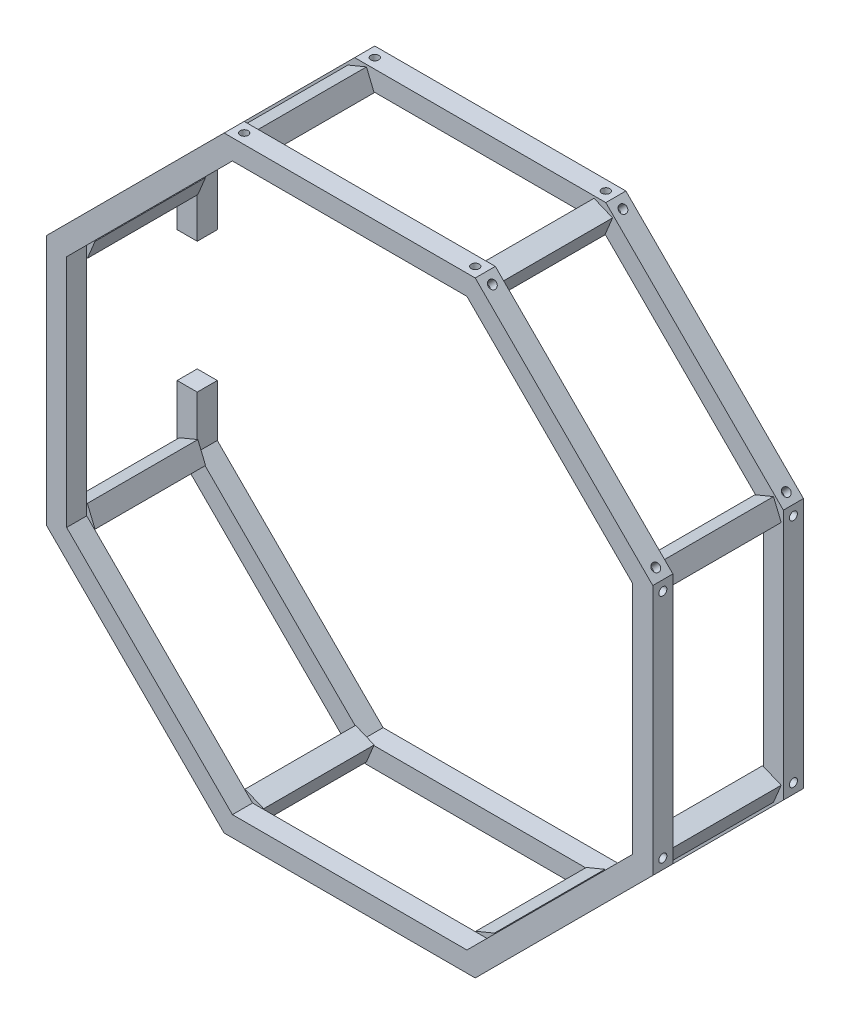
SolidWorks part; units mm, degrees
ref_plane "Front Plane" through (0, 0, 0) normal (0, 0, 1) x (1, 0, 0)
ref_plane "Top Plane" through (0, 0, 0) normal (0, 1, 0) x (1, 0, 0)
ref_plane "Right Plane" through (0, 0, 0) normal (1, 0, 0) x (0, 0, -1)
sketch "Sketch1" plane through (0, 0, 0) normal (0, 0, 1) x (1, 0, 0)
  line L7 (301.7767, 125) -> (125, 301.7767)
  line L8 (125, 301.7767) -> (-125, 301.7767)
  line L9 (-125, 301.7767) -> (-301.7767, 125)
  line L10 (-301.7767, 125) -> (-301.7767, -125)
  line L11 (-301.7767, -125) -> (-125, -301.7767)
  line L12 (-125, -301.7767) -> (125, -301.7767)
  line L13 (125, -301.7767) -> (301.7767, -125)
  line L14 (301.7767, -125) -> (301.7767, 125)
  line L15 (-281.7767, 116.7157) -> (-281.7767, -116.7157)
  line L16 (-281.7767, -116.7157) -> (-116.7157, -281.7767)
  line L17 (-116.7157, -281.7767) -> (116.7157, -281.7767)
  line L18 (116.7157, -281.7767) -> (281.7767, -116.7157)
  line L19 (281.7767, -116.7157) -> (281.7767, 116.7157)
  line L20 (281.7767, 116.7157) -> (116.7157, 281.7767)
  line L21 (116.7157, 281.7767) -> (-116.7157, 281.7767)
  line L22 (-116.7157, 281.7767) -> (-281.7767, 116.7157)
  circle A0 centre (0, 0) radius 281.7767 construction
  circle A1 centre (0, 0) radius 301.7767 construction
  dimension "D1" = 250
  dimension "D2" = 20
extrude "Boss-Extrude1" add sketch "Sketch1" along normal blind 20 separate body contours L7 L8 L9 L10 L11 L12 L13 L14 | L15 L16 L17 L18 L19 L20 L21 L22
sketch "Sketch14" plane through (0, 0, 0) normal (0, 0, 1) x (1, 0, 0)
  line L7 (300, 124.2641) -> (124.2641, 300)
  line L8 (124.2641, 300) -> (-124.2641, 300)
  line L9 (-124.2641, 300) -> (-300, 124.2641)
  line L10 (-300, 124.2641) -> (-300, -124.2641)
  line L11 (-300, -124.2641) -> (-124.2641, -300)
  line L12 (-124.2641, -300) -> (124.2641, -300)
  line L13 (124.2641, -300) -> (300, -124.2641)
  line L14 (300, -124.2641) -> (300, 124.2641)
  line L15 (-277.1639, 114.805) -> (-277.1639, -114.805)
  line L16 (-277.1639, -114.805) -> (-114.805, -277.1639)
  line L17 (-114.805, -277.1639) -> (114.805, -277.1639)
  line L18 (114.805, -277.1639) -> (277.1639, -114.805)
  line L19 (277.1639, -114.805) -> (277.1639, 114.805)
  line L20 (277.1639, 114.805) -> (114.805, 277.1639)
  line L21 (114.805, 277.1639) -> (-114.805, 277.1639)
  line L22 (-114.805, 277.1639) -> (-277.1639, 114.805)
  circle A0 centre (0, 0) radius 277.1639 construction
  circle A1 centre (0, 0) radius 300 construction
  dimension "D2" = 600
sketch "Sketch17" plane through (0, 0, 20) normal (0, 0, 1) x (1, 0, 0)
  line L0 (-146.9098, 264.0383) -> (-60.0907, 300) construction
  line L1 (-124.1049, 273.4844) -> (-105.6273, 281.1381)
  line L2 (-124.1049, 273.4844) -> (-131.7586, 291.962)
  line L3 (-105.6273, 281.1381) -> (-113.281, 299.6157)
  line L4 (-131.7586, 291.962) -> (-113.281, 299.6157)
  line L5 (124.2641, 300) -> (-124.2641, 300) construction
  line L18 (0, 0) -> (-124.2641, 300) construction
  line L19 (0, 0) -> (124.2641, 300) construction
  line L20 (105.6273, 281.1381) -> (124.1049, 273.4844)
  line L21 (105.6273, 281.1381) -> (113.281, 299.6157)
  line L22 (113.281, 299.6157) -> (131.7586, 291.962)
  line L23 (124.1049, 273.4844) -> (131.7586, 291.962)
  line L24 (273.4844, 124.1049) -> (281.1381, 105.6273)
  line L25 (273.4844, 124.1049) -> (291.962, 131.7586)
  line L26 (291.962, 131.7586) -> (299.6157, 113.281)
  line L27 (281.1381, 105.6273) -> (299.6157, 113.281)
  line L28 (281.1381, -105.6273) -> (273.4844, -124.1049)
  line L29 (281.1381, -105.6273) -> (299.6157, -113.281)
  line L30 (299.6157, -113.281) -> (291.962, -131.7586)
  line L31 (273.4844, -124.1049) -> (291.962, -131.7586)
  line L32 (124.1049, -273.4844) -> (105.6273, -281.1381)
  line L33 (124.1049, -273.4844) -> (131.7586, -291.962)
  line L34 (131.7586, -291.962) -> (113.281, -299.6157)
  line L35 (105.6273, -281.1381) -> (113.281, -299.6157)
  line L36 (-105.6273, -281.1381) -> (-124.1049, -273.4844)
  line L37 (-105.6273, -281.1381) -> (-113.281, -299.6157)
  line L38 (-113.281, -299.6157) -> (-131.7586, -291.962)
  line L39 (-124.1049, -273.4844) -> (-131.7586, -291.962)
  line L40 (-273.4844, -124.1049) -> (-281.1381, -105.6273)
  line L41 (-273.4844, -124.1049) -> (-291.962, -131.7586)
  line L42 (-291.962, -131.7586) -> (-299.6157, -113.281)
  line L43 (-281.1381, -105.6273) -> (-299.6157, -113.281)
  line L44 (-281.1381, 105.6273) -> (-273.4844, 124.1049)
  line L45 (-281.1381, 105.6273) -> (-299.6157, 113.281)
  line L46 (-299.6157, 113.281) -> (-291.962, 131.7586)
  line L47 (-273.4844, 124.1049) -> (-291.962, 131.7586)
  point P23 (0, 0)
  point P59 (0, 0)
  dimension "D1" = 20
  dimension "D2" = 10
  dimension "D3" = 10
  dimension "D4" = 8
extrude "Boss-Extrude3" add sketch "Sketch17" along normal blind 110 separate body
sketch "Sketch18" plane through (0, 0, 130) normal (0, 0, 1) x (1, 0, 0)
  line L1 (-301.7767, 125) -> (-301.7767, -125)
  line L2 (-301.7767, -125) -> (-125, -301.7767)
  line L3 (-125, -301.7767) -> (125, -301.7767)
  line L4 (125, -301.7767) -> (301.7767, -125)
  line L5 (301.7767, -125) -> (301.7767, 125)
  line L6 (301.7767, 125) -> (125, 301.7767)
  line L7 (125, 301.7767) -> (-125, 301.7767)
  line L8 (-125, 301.7767) -> (-301.7767, 125)
  line L9 (-281.7767, 116.7157) -> (-281.7767, -116.7157)
  line L10 (-281.7767, -116.7157) -> (-116.7157, -281.7767)
  line L11 (-116.7157, -281.7767) -> (116.7157, -281.7767)
  line L12 (116.7157, -281.7767) -> (281.7767, -116.7157)
  line L13 (281.7767, -116.7157) -> (281.7767, 116.7157)
  line L14 (281.7767, 116.7157) -> (116.7157, 281.7767)
  line L15 (116.7157, 281.7767) -> (-116.7157, 281.7767)
  line L16 (-116.7157, 281.7767) -> (-281.7767, 116.7157)
  circle A0 centre (0, 0) radius 301.7767 construction
  circle A1 centre (0, 0) radius 281.7767 construction
  dimension "D1" = 250
  dimension "D2" = 20
extrude "Boss-Extrude4" add sketch "Sketch18" along normal blind 20 separate body
sketch "Sketch19" plane through (0, -301.7767, 0) normal (0, -1, 0) x (1, 0, 0)
  line L0 (0, 0) -> (0, 247.429) construction
  line L1 (-125, 150) -> (125, 150) construction
  line L2 (-125, 150) -> (-125, 130) construction
  line L3 (-125, 20) -> (125, 20) construction
  line L4 (-125, 20) -> (-125, 0) construction
  circle A0 centre (-115, 140) radius 4
  circle A1 centre (-115, 10) radius 4
  circle A2 centre (115, 140) radius 4
  circle A3 centre (115, 10) radius 4
  dimension "D1" = 10
  dimension "D2" = 10
  dimension "D3" = 8
  dimension "D4" = 10
  dimension "D5" = 10
  dimension "D6" = 8
extrude "Cut-Extrude1" cut sketch "Sketch19" against normal blind 10
sketch "Sketch29" plane through (213.3883, -213.3883, 0) normal (0.7071, -0.7071, 0) x (0, 0, -1)
  line L0 (0, 0) -> (118.9381, 0) construction
  line L1 (-150, 125) -> (-130, 125) construction
  line L2 (-20, 125) -> (0, 125) construction
  line L3 (-20, -125) -> (-20, 125) construction
  line L4 (-130, -125) -> (-130, 125) construction
  circle A0 centre (-140, 115) radius 4
  circle A1 centre (-10, 115) radius 4
  circle A2 centre (-10, -115) radius 4
  circle A3 centre (-140, -115) radius 4
  dimension "D1" = 8
  dimension "D2" = 10
  dimension "D3" = 8
  dimension "D4" = 10
  dimension "D5" = 10
  dimension "D6" = 10
extrude "Cut-Extrude2" cut sketch "Sketch29" against normal blind 10
sketch "Sketch30" plane through (301.7767, 0, 0) normal (1, 0, 0) x (0, 0, -1)
  line L0 (224.3908, 0) -> (343.3289, 0) construction
  line L1 (-150, -125) -> (-150, 125) construction
  line L2 (-150, 125) -> (-130, 125) construction
  line L3 (-20, -125) -> (-20, 125) construction
  line L4 (-20, 125) -> (0, 125) construction
  line L5 (-150, -125) -> (-130, -125) construction
  line L6 (-20, -125) -> (0, -125) construction
  circle A0 centre (-140, 115) radius 4
  circle A1 centre (-10, 115) radius 4
  circle A2 centre (-10, -115) radius 4
  circle A3 centre (-140, -115) radius 4
  dimension "D1" = 8
  dimension "D2" = 8
  dimension "D3" = 10
  dimension "D4" = 10
  dimension "D5" = 10
  dimension "D6" = 10
  dimension "D7" = 10
  dimension "D8" = 10
extrude "Cut-Extrude3" cut sketch "Sketch30" against normal blind 10
sketch "Sketch31" plane through (213.3883, 213.3883, 0) normal (0.7071, 0.7071, 0) x (0, 0, -1)
  line L0 (-1.0204, 0) -> (117.9177, 0) construction
  line L1 (-150, 125) -> (-130, 125) construction
  line L2 (-20, 125) -> (0, 125) construction
  line L3 (-150, -125) -> (-150, 125) construction
  line L4 (0, -125) -> (0, 125) construction
  line L5 (-150, -125) -> (-130, -125) construction
  circle A0 centre (-140, 115) radius 4
  circle A1 centre (-10, 115) radius 4
  circle A2 centre (-10, -115) radius 4
  circle A3 centre (-140, -115) radius 4
  dimension "D1" = 8
  dimension "D2" = 8
  dimension "D3" = 10
  dimension "D4" = 10
  dimension "D5" = 10
  dimension "D6" = 10
  dimension "D7" = 10
extrude "Cut-Extrude4" cut sketch "Sketch31" against normal blind 10
sketch "Sketch32" plane through (0, 301.7767, 0) normal (0, 1, 0) x (1, 0, 0)
  line L0 (0, 0) -> (0, -189.5447) construction
  line L1 (125, 0) -> (-125, 0) construction
  line L2 (-125, -20) -> (-125, 0) construction
  line L3 (125, -150) -> (-125, -150) construction
  line L4 (-125, -150) -> (-125, -130) construction
  circle A0 centre (-115, -10) radius 4
  circle A1 centre (-115, -140) radius 4
  circle A2 centre (115, -140) radius 4
  circle A3 centre (115, -10) radius 4
  dimension "D1" = 10
  dimension "D2" = 8
  dimension "D3" = 10
  dimension "D4" = 8
  dimension "D5" = 10
  dimension "D6" = 10
extrude "Cut-Extrude5" cut sketch "Sketch32" against normal blind 10
sketch "Sketch33" plane through (-213.3883, 213.3883, 0) normal (-0.7071, 0.7071, 0) x (0, 0, 1)
  line L0 (0, 0) -> (266.3624, 0) construction
  line L1 (20, 125) -> (0, 125) construction
  line L2 (150, 125) -> (130, 125) construction
  line L3 (150, 125) -> (150, -125) construction
  line L4 (0, 125) -> (0, -125) construction
  circle A0 centre (10, 115) radius 4
  circle A1 centre (140, 115) radius 4
  circle A2 centre (140, -115) radius 4
  circle A3 centre (10, -115) radius 4
  dimension "D1" = 8
  dimension "D2" = 8
  dimension "D3" = 10
  dimension "D4" = 10
  dimension "D5" = 10
  dimension "D6" = 10
extrude "Cut-Extrude6" cut sketch "Sketch33" against normal blind 10
sketch "Sketch34" plane through (-301.7767, 0, 0) normal (-1, 0, 0) x (0, 0, 1)
  line L0 (0, 0) -> (273.85, 0) construction
  line L1 (20, 125) -> (0, 125) construction
  line L2 (0, 125) -> (0, -125) construction
  line L3 (150, 125) -> (130, 125) construction
  line L4 (130, 125) -> (130, -125) construction
  circle A0 centre (10, 115) radius 4
  circle A1 centre (140, 115) radius 4
  circle A2 centre (140, -115) radius 4
  circle A3 centre (10, -115) radius 4
  dimension "D1" = 8
  dimension "D2" = 8
  dimension "D3" = 10
  dimension "D4" = 10
  dimension "D5" = 10
  dimension "D6" = 10
extrude "Cut-Extrude7" cut sketch "Sketch34" against normal blind 10
sketch "Sketch35" plane through (-213.3883, -213.3883, 0) normal (-0.7071, -0.7071, 0) x (0, 0, 1)
  line L0 (0, 0) -> (267.6314, 0) construction
  line L1 (0, 125) -> (0, -125) construction
  line L2 (150, 125) -> (150, -125) construction
  line L3 (20, 125) -> (0, 125) construction
  line L4 (150, 125) -> (130, 125) construction
  circle A0 centre (10, 115) radius 4
  circle A1 centre (140, 115) radius 4
  circle A2 centre (140, -115) radius 4
  circle A3 centre (10, -115) radius 4
  dimension "D1" = 8
  dimension "D2" = 8
  dimension "D3" = 10
  dimension "D4" = 10
  dimension "D5" = 10
  dimension "D6" = 10
extrude "Cut-Extrude8" cut sketch "Sketch35" against normal blind 10
sketch "Sketch36" plane through (0, 301.7767, 0) normal (0, 1, 0) x (1, 0, 0)
  line L2 (-65, 73.0804) -> (65, 73.0804)
  line L3 (-65, 73.0804) -> (-65, -20)
  line L4 (-65, -20) -> (65, -20)
  line L5 (65, 73.0804) -> (65, -20)
  line L7 (0, 0) -> (0, -99.3594) construction
  line L9 (-100.4574, 73.0804) -> (154.5426, 73.0804) construction
  dimension "D1" = 130
  dimension "D2" = 65
sketch "Sketch37" plane through (-301.7767, 0, 0) normal (-1, 0, 0) x (0, 0, 1)
  line L0 (0, 125) -> (0, -125) construction
  line L1 (0, -65.0018) -> (20, -65.0018)
  line L2 (0, -65.0018) -> (0, 65)
  line L3 (0, 65) -> (20, 65)
  line L4 (20, -65.0018) -> (20, 65)
  line L5 (20, 125) -> (20, -125) construction
  dimension "D1" = 65.0018
  dimension "D2" = 65
extrude "Cut-Extrude11" cut sketch "Sketch37" against normal blind 20 contours L2 L1 L4 L3
